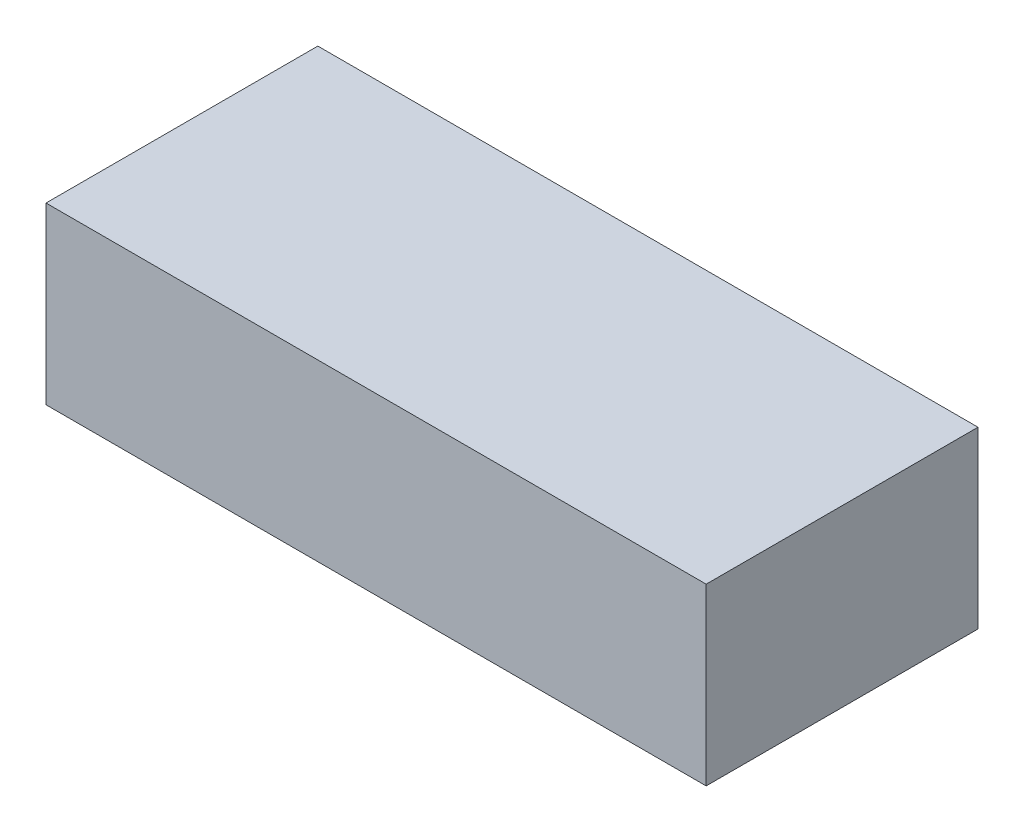
SolidWorks part; units mm, degrees
material "未指定"
ref_plane "正面" through (0, 0, 0) normal (0, 0, 1) x (1, 0, 0)
ref_plane "平面" through (0, 0, 0) normal (0, 1, 0) x (1, 0, 0)
ref_plane "右側面" through (0, 0, 0) normal (1, 0, 0) x (0, 0, -1)
sketch "ｽｹｯﾁ1" plane through (0, 0, 0) normal (0, 1, 0) x (1, 0, 0)
  line L0 (-85, 35) -> (85, 35)
  line L1 (85, 35) -> (85, -35)
  line L2 (85, -35) -> (-85, -35)
  line L3 (-85, -35) -> (-85, 35)
  line L4 (0, 0) -> (0, -25) construction
  line L5 (0, 0) -> (25, 0) construction
  dimension "D1" = 170
  dimension "D2" = 70
extrude "外形" add sketch "ｽｹｯﾁ1" along normal mid plane 45
equation "\"BATT_L\" = 170"
equation "\"D1@ｽｹｯﾁ1\" = \"BATT_L\""
equation "\"BATT_W\" = 70"
equation "\"D2@ｽｹｯﾁ1\" = \"BATT_W\""
equation "\"BATT_H\" = 45"
equation "\"D1@外形\" = \"BATT_H\""
